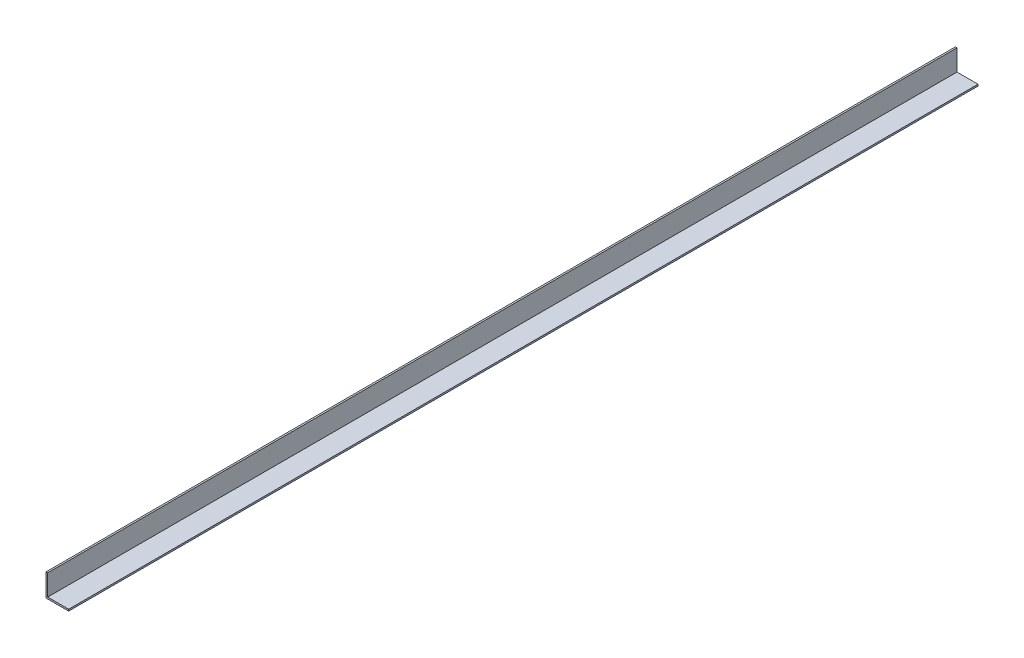
SolidWorks part; units mm, degrees
material "ASTM A36 Acero"
ref_plane "Alzado" through (0, 0, 0) normal (0, 0, 1) x (1, 0, 0)
ref_plane "Planta" through (0, 0, 0) normal (0, 1, 0) x (1, 0, 0)
ref_plane "Vista lateral" through (0, 0, 0) normal (1, 0, 0) x (0, 0, -1)
sketch "Croquis1" plane through (0, 0, 0) normal (0, 0, 1) x (1, 0, 0)
  line L0 (0, 152) -> (0, 0)
  line L1 (0, 0) -> (152, 0)
  line L2 (152, 0) -> (152, 11.1)
  line L3 (152, 11.1) -> (11.1, 11.1)
  line L4 (11.1, 11.1) -> (11.1, 152)
  line L5 (11.1, 152) -> (0, 152)
  dimension "D1" = 11.1
  dimension "D2" = 152
extrude "Saliente-Extruir1" add sketch "Croquis1" against normal blind 6100
